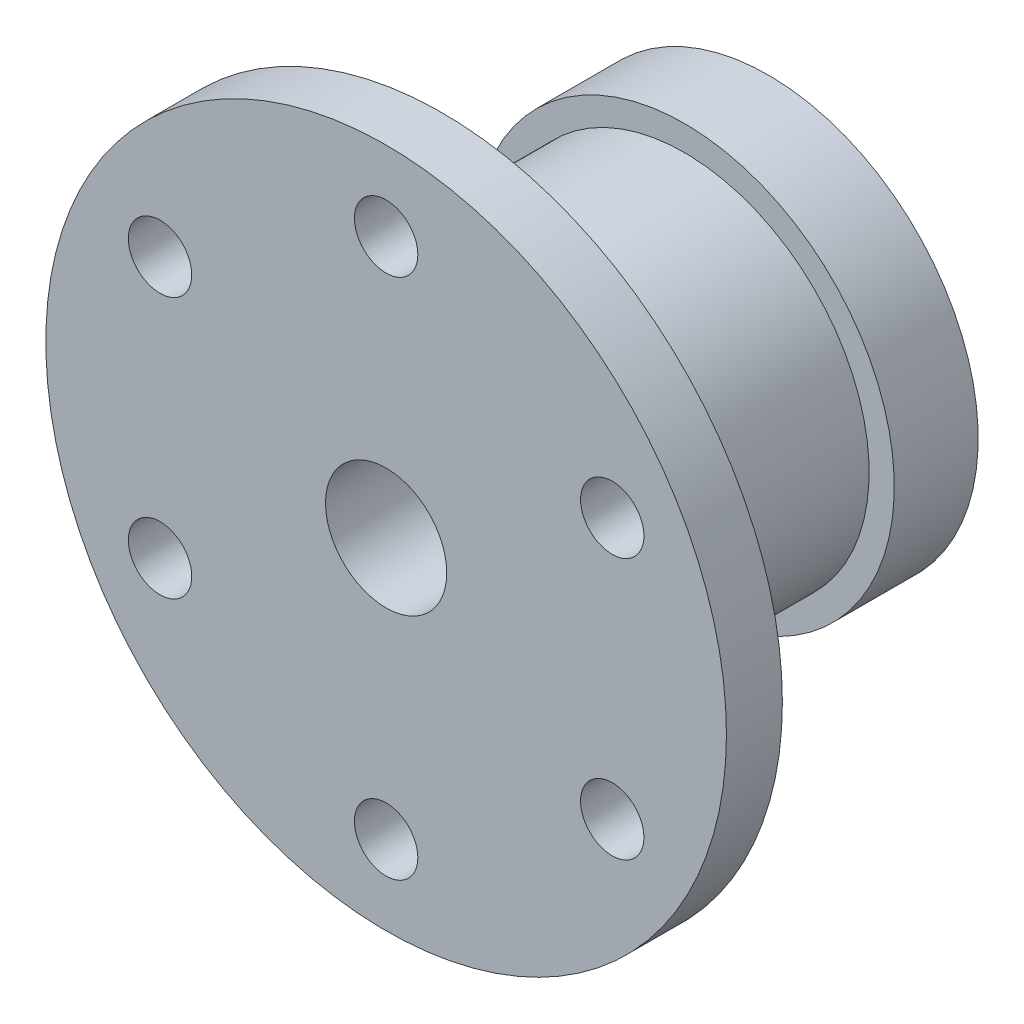
SolidWorks part; units mm, degrees
ref_plane "前视基准面" through (0, 0, 0) normal (0, 0, 1) x (1, 0, 0)
ref_plane "上视基准面" through (0, 0, 0) normal (0, 1, 0) x (1, 0, 0)
ref_plane "右视基准面" through (0, 0, 0) normal (1, 0, 0) x (0, 0, -1)
other "Configuration Table"
sketch "轴承端法兰_Ø36.5_厚3_草图" plane through (0, 0, 0) normal (0, 0, 1) x (1, 0, 0)
  circle A0 centre (0, 0) radius 18.25
  circle A1 centre (0, 0) radius 3.25
extrude "轴承端法兰_Ø36.5_厚3" add sketch "轴承端法兰_Ø36.5_厚3_草图" along normal blind 3
sketch "穿轴颈_Ø19.8_长17.5_草图" plane through (0, 0, 0) normal (0, 0, -1) x (-1, 0, 0)
  circle A0 centre (0, 0) radius 9.9
  circle A1 centre (0, 0) radius 3.25
extrude "穿轴颈_Ø19.8_长17.5" add sketch "穿轴颈_Ø19.8_长17.5_草图" along normal blind 17.5
sketch "舵盘端凸缘_Ø22.5_长4.5_草图" plane through (0, 0, -17.5) normal (0, 0, -1) x (-1, 0, 0)
  circle A0 centre (0, 0) radius 11.25
  circle A1 centre (0, 0) radius 3.25
extrude "舵盘端凸缘_Ø22.5_长4.5" add sketch "舵盘端凸缘_Ø22.5_长4.5_草图" against normal blind 4.5
sketch "轴承端_六处Ø3.4_分度圆Ø28_草图" plane through (0, 0, 3) normal (0, 0, 1) x (1, 0, 0)
  circle A0 centre (12.1244, 7) radius 1.7
  circle A1 centre (0, 14) radius 1.7
  circle A2 centre (-12.1244, 7) radius 1.7
  circle A3 centre (-12.1244, -7) radius 1.7
  circle A4 centre (0, -14) radius 1.7
  circle A5 centre (12.1244, -7) radius 1.7
extrude "轴承端_六处Ø3.4_分度圆Ø28" cut sketch "轴承端_六处Ø3.4_分度圆Ø28_草图" against normal blind 3
sketch "舵盘止口_Ø20.35_深0.6_草图" plane through (0, 0, -17.5) normal (0, 0, -1) x (-1, 0, 0)
  circle A0 centre (0, 0) radius 10.175
extrude "舵盘止口_Ø20.35_深0.6" cut sketch "舵盘止口_Ø20.35_深0.6_草图" against normal blind 0.6
sketch "现有舵盘_四处M2x0.4_分度圆Ø14.142_草图" plane through (0, 0, -16.9) normal (0, 0, -1) x (-1, 0, 0)
  circle A0 centre (-7.0711, 0) radius 0.8
  circle A1 centre (0, 7.0711) radius 0.8
  circle A2 centre (7.0711, 0) radius 0.8
  circle A3 centre (0, -7.0711) radius 0.8
extrude "现有舵盘_四处M2x0.4_分度圆Ø14.142" cut sketch "现有舵盘_四处M2x0.4_分度圆Ø14.142_草图" against normal blind 5
